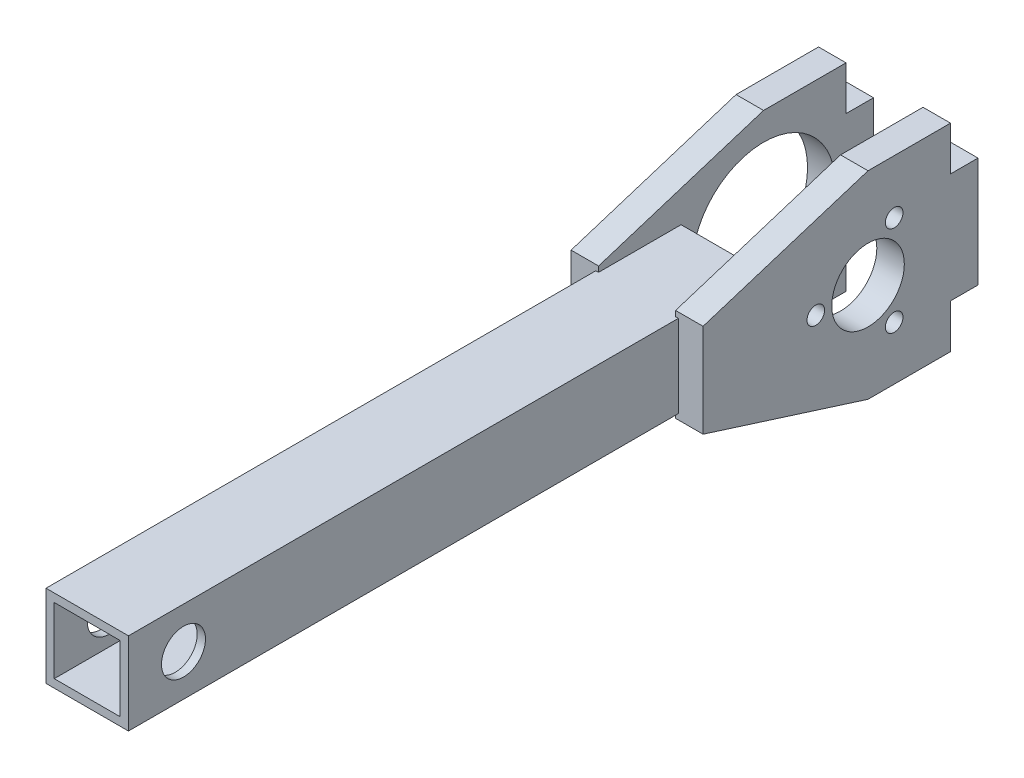
SolidWorks part; units mm, degrees
ref_plane "正面" through (0, 0, 0) normal (0, 0, 1) x (1, 0, 0)
ref_plane "平面" through (0, 0, 0) normal (0, 1, 0) x (1, 0, 0)
ref_plane "右側面" through (0, 0, 0) normal (1, 0, 0) x (0, 0, -1)
sketch "ｽｹｯﾁ1" plane through (0, 0, 0) normal (0, 0, 1) x (1, 0, 0)
  circle A0 centre (0, 0) radius 23.5 construction
  circle A1 centre (0, 0) radius 20 construction
  circle A2 centre (0, 20) radius 1.6 construction
  circle A3 centre (20, 0) radius 1.6 construction
  circle A4 centre (0, -20) radius 1.6 construction
  circle A5 centre (-20, 0) radius 1.6 construction
  point P15 (0, 0)
  dimension "D1" = 40
  dimension "47" = 47
  dimension "D2" = 3.2
  dimension "D3" = 4
ref_plane "arm_link1_m2006_mount_surface" through (7, 0, 0) normal (1, 0, 0) x (0, 0, -1)
ref_plane "arm_link1_axis_hold_mount_surface" through (-7, 0, 0) normal (1, 0, 0) x (0, 0, -1)
sketch "ｽｹｯﾁ3" plane through (7, 0, 0) normal (1, 0, 0) x (0, 0, -1)
  line L0 (0, 0) -> (-45, 0) construction
  line L1 (5, 10) -> (5, -10)
  line L2 (5, -10) -> (0, -10)
  line L3 (0, -10) -> (0, -18)
  line L4 (0, -18) -> (-15, -18)
  line L5 (-15, -18) -> (-45, -8.5)
  line L6 (-45, -8.5) -> (-45, 8.5)
  line L7 (-15, 18) -> (-45, 8.5)
  line L8 (0, 18) -> (-15, 18)
  line L9 (0, 10) -> (0, 18)
  line L10 (5, 10) -> (0, 10)
  circle A0 centre (-15, 0) radius 9.5 construction
  circle A1 centre (-15, 0) radius 6.6
  circle A2 centre (-24.5, 0) radius 1.6
  circle A3 centre (-10.25, 8.2272) radius 1.6
  circle A4 centre (-10.25, -8.2272) radius 1.6
  point P17 (5, 0)
  point P26 (-15, 0)
  dimension "D7" = 19
  dimension "D8" = 13.2
  dimension "D9" = 3.2
  dimension "D1" = 8.5
  dimension "D2" = 10
  dimension "D3" = 8
  dimension "D4" = 15
  dimension "D5" = 45
  dimension "D6" = 5
  dimension "D10" = 3
extrude "ﾎﾞｽ - 押し出し1" add sketch "ｽｹｯﾁ3" along normal blind 5
sketch "ｽｹｯﾁ5" plane through (-7, 0, 0) normal (1, 0, 0) x (0, 0, -1)
  line L0 (0, 0) -> (-53.7832, 0) construction
  line L1 (-45, -8.5) -> (-45, 8.5)
  line L2 (-45, 8.5) -> (-15, 18)
  line L3 (-15, 18) -> (0, 18)
  line L4 (0, 18) -> (0, 10)
  line L5 (0, 10) -> (5, 10)
  line L6 (5, 10) -> (5, -10)
  line L8 (-45, 8.5) -> (-45, -8.5) construction
  line L9 (0, -10) -> (5, -10)
  line L10 (0, -18) -> (0, -10)
  line L11 (-15, -18) -> (0, -18)
  line L12 (-45, -8.5) -> (-15, -18)
  circle A0 centre (-15, 0) radius 13
  point P19 (5, 0)
  point P23 (-45, 0)
  dimension "D6" = 26
  dimension "D1" = 5
  dimension "D2" = 10
  dimension "D3" = 8
  dimension "D4" = 8.5
  dimension "D5" = 15
extrude "ﾎﾞｽ - 押し出し2" add sketch "ｽｹｯﾁ5" against normal blind 5 separate body
sketch "ｽｹｯﾁ6" plane through (0, 0, 45) normal (0, 0, 1) x (1, 0, 0)
  line L1 (7.5, -7.5) -> (-7.5, -7.5)
  line L2 (7.5, -7.5) -> (7.5, 7.5)
  line L3 (7.5, 7.5) -> (-7.5, 7.5)
  line L4 (-7.5, -7.5) -> (-7.5, 7.5)
  line L6 (0, -25.85) -> (0, 25.85) construction
  line L7 (25.85, 0) -> (-25.85, 0) construction
  line L8 (6, -6) -> (-6, -6)
  line L9 (-6, -6) -> (-6, 6)
  line L10 (6, 6) -> (-6, 6)
  line L11 (6, -6) -> (6, 6)
  dimension "D1" = 15
  dimension "D2" = 7.5
  dimension "D3" = 7.5
  dimension "D4" = 1.5
extrude "ﾎﾞｽ - 押し出し3" add sketch "ｽｹｯﾁ6" against normal blind 15 and the other way blind 100
sketch "ｽｹｯﾁ7" plane through (7.5, 0, 0) normal (1, 0, 0) x (0, 0, -1)
  line L0 (-135, -7.5) -> (-135, 7.5) construction
  line L1 (-145, -7.5) -> (-45, -7.5) construction
  line L2 (-145, 7.5) -> (-45, 7.5) construction
  line L3 (-145, -7.5) -> (-145, 7.5) construction
  circle A0 centre (-135, 0) radius 4
  dimension "D2" = 8
  dimension "D1" = 10
extrude "ｶｯﾄ - 押し出し1" cut sketch "ｽｹｯﾁ7" against normal through all
